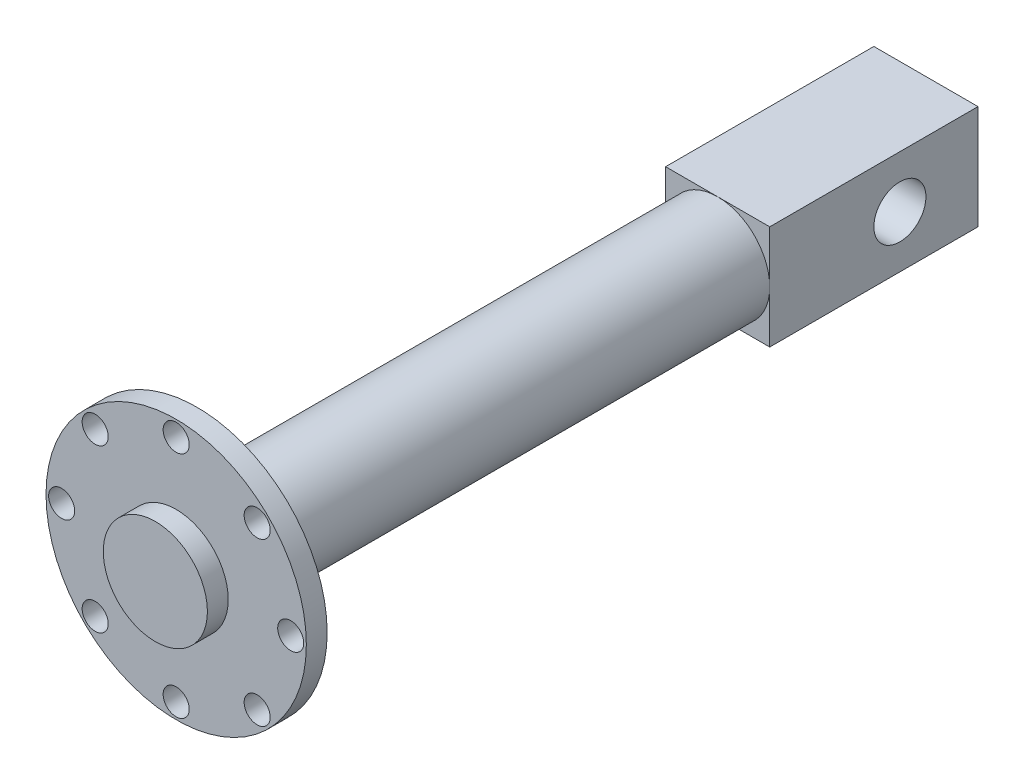
SolidWorks part; units mm, degrees
ref_plane "Ebene vorne" through (0, 0, 0) normal (0, 0, 1) x (1, 0, 0)
ref_plane "Ebene oben" through (0, 0, 0) normal (0, 1, 0) x (1, 0, 0)
ref_plane "Ebene rechts" through (0, 0, 0) normal (1, 0, 0) x (0, 0, -1)
sketch "Skizze1" plane through (0, 0, 0) normal (0, 0, 1) x (1, 0, 0)
  line L1 (-5, 5) -> (5, 5)
  line L2 (-5, 5) -> (-5, -5)
  line L3 (-5, -5) -> (5, -5)
  line L4 (5, 5) -> (5, -5)
  line L5 (-5, 5) -> (5, -5) construction
  line L6 (-5, -5) -> (5, 5) construction
  point P0 (0, 0)
  dimension "D1" = 10
  dimension "D2" = 10
extrude "Aufsatz-Linear austragen1" add sketch "Skizze1" along normal blind 20
sketch "Skizze2" plane through (5, 0, 0) normal (1, 0, 0) x (0, 0, -1)
  line L0 (0, -5) -> (0, 5) construction
  line L1 (-20, -5) -> (0, -5) construction
  circle A0 centre (-7.5, 0) radius 2.5
  dimension "D2" = 5
  dimension "D3" = 5
  dimension "D1" = 7.5
extrude "Schnitt-Linear austragen1" cut sketch "Skizze2" against normal blind 20
sketch "Skizze3" plane through (0, 0, 20) normal (0, 0, 1) x (1, 0, 0)
  circle A0 centre (0, 0) radius 5
extrude "Aufsatz-Linear austragen2" add sketch "Skizze3" along normal blind 50
sketch "Skizze4" plane through (0, 0, 70) normal (0, 0, 1) x (1, 0, 0)
  circle A0 centre (0, 0) radius 12.5
  dimension "D1" = 25
extrude "Aufsatz-Linear austragen3" add sketch "Skizze4" along normal blind 2
sketch "Skizze5" plane through (0, 0, 72) normal (0, 0, 1) x (1, 0, 0)
  line L0 (0, 0) -> (0, 12.0407) construction
  circle A0 centre (0, 11) radius 1.25
  circle A1 centre (7.7782, 7.7782) radius 1.25
  circle A2 centre (11, 0) radius 1.25
  circle A3 centre (7.7782, -7.7782) radius 1.25
  circle A4 centre (0, -11) radius 1.25
  circle A5 centre (-7.7782, -7.7782) radius 1.25
  circle A6 centre (-11, 0) radius 1.25
  circle A7 centre (-7.7782, 7.7782) radius 1.25
  point P21 (0, 0)
  dimension "D3" = 2.5
  dimension "D1" = 11
  dimension "D2" = 8
extrude "Schnitt-Linear austragen2" cut sketch "Skizze5" against normal blind 5
sketch "Skizze6" plane through (0, 0, 72) normal (0, 0, 1) x (1, 0, 0)
  circle A0 centre (0, 0) radius 5
extrude "Aufsatz-Linear austragen4" add sketch "Skizze6" along normal blind 2
